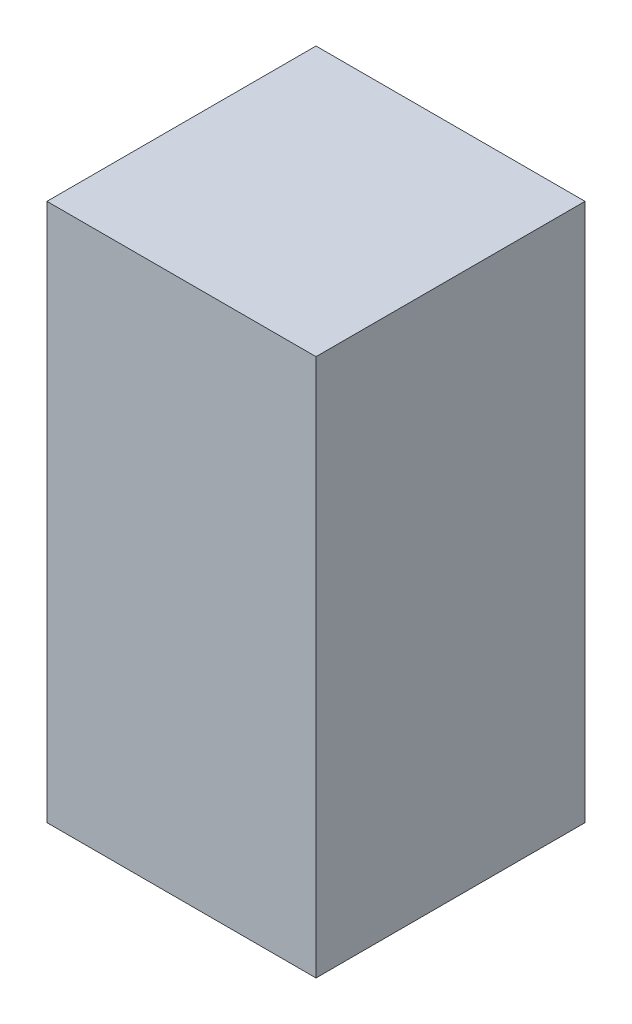
SolidWorks part; units mm, degrees
ref_plane "Front Plane" through (0, 0, 0) normal (0, 0, 1) x (1, 0, 0)
ref_plane "Top Plane" through (0, 0, 0) normal (0, 1, 0) x (1, 0, 0)
ref_plane "Right Plane" through (0, 0, 0) normal (1, 0, 0) x (0, 0, -1)
other "Configuration Table"
sketch "Sketch1" plane through (0, 0, 0) normal (0, 0, 1) x (1, 0, 0)
  line L1 (535, 470) -> (565, 470)
  line L2 (535, 470) -> (535, 530)
  line L3 (535, 530) -> (565, 530)
  line L4 (565, 470) -> (565, 530)
extrude "PACK_lineer_rulman_2_1" add sketch "Sketch1" against normal blind 30 from offset 385 separate body
